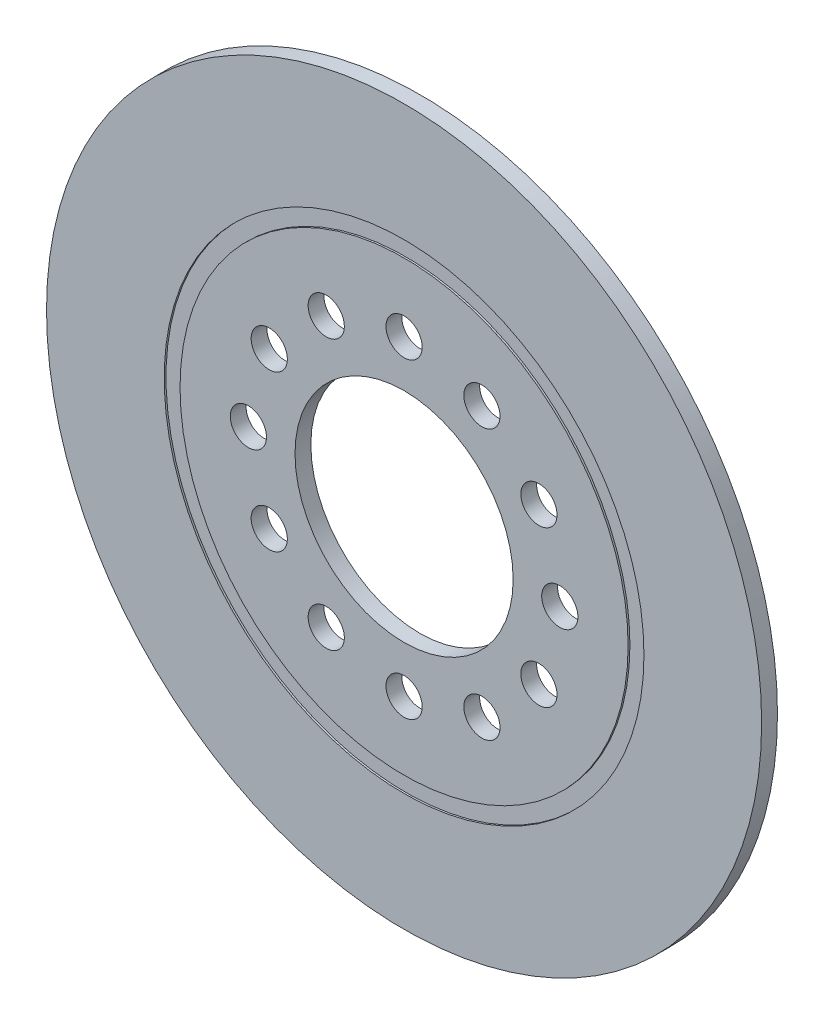
SolidWorks part; units mm, degrees
ref_plane "Front Plane" through (0, 0, 0) normal (0, 0, 1) x (1, 0, 0)
ref_plane "Top Plane" through (0, 0, 0) normal (0, 1, 0) x (1, 0, 0)
ref_plane "Right Plane" through (0, 0, 0) normal (1, 0, 0) x (0, 0, -1)
sketch "Sketch1" plane through (0, 0, 0) normal (0, 0, 1) x (1, 0, 0)
  circle A0 centre (0, 0) radius 79
extrude "Boss-Extrude1" add sketch "Sketch1" along normal blind 3.5
sketch "Sketch2" plane through (0, 0, 0) normal (0, 0, 1) x (1, 0, 0)
  line L0 (0, 0) -> (30.375, 0) construction
  line L1 (0, 0) -> (38.42, 0) construction
  circle A0 centre (34.4, 0) radius 4
  circle A1 centre (29.7913, -17.2) radius 4
  circle A2 centre (17.2, -29.7913) radius 4
  circle A3 centre (0, -34.4) radius 4
  circle A4 centre (-17.2, -29.7913) radius 4
  circle A5 centre (-29.7913, -17.2) radius 4
  circle A6 centre (-34.4, 0) radius 4
  circle A7 centre (-29.7913, 17.2) radius 4
  circle A8 centre (-17.2, 29.7913) radius 4
  circle A9 centre (0, 34.4) radius 4
  circle A10 centre (17.2, 29.7913) radius 4
  circle A11 centre (29.7913, 17.2) radius 4
  circle A12 centre (0, 0) radius 24.1
  point P30 (0, 0)
  dimension "D4" = 12
  dimension "D1" = 30.375
  dimension "D2" = 38.42
  dimension "D3" = 34.4
extrude "Cut-Extrude1" cut sketch "Sketch2" along normal through all
sketch "Sketch3" plane through (0, 0, 3.5) normal (0, 0, 1) x (1, 0, 0)
  circle A0 centre (0, 0) radius 49.5
  circle A1 centre (0, 0) radius 53
extrude "Cut-Extrude2" cut sketch "Sketch3" against normal blind 0.4
